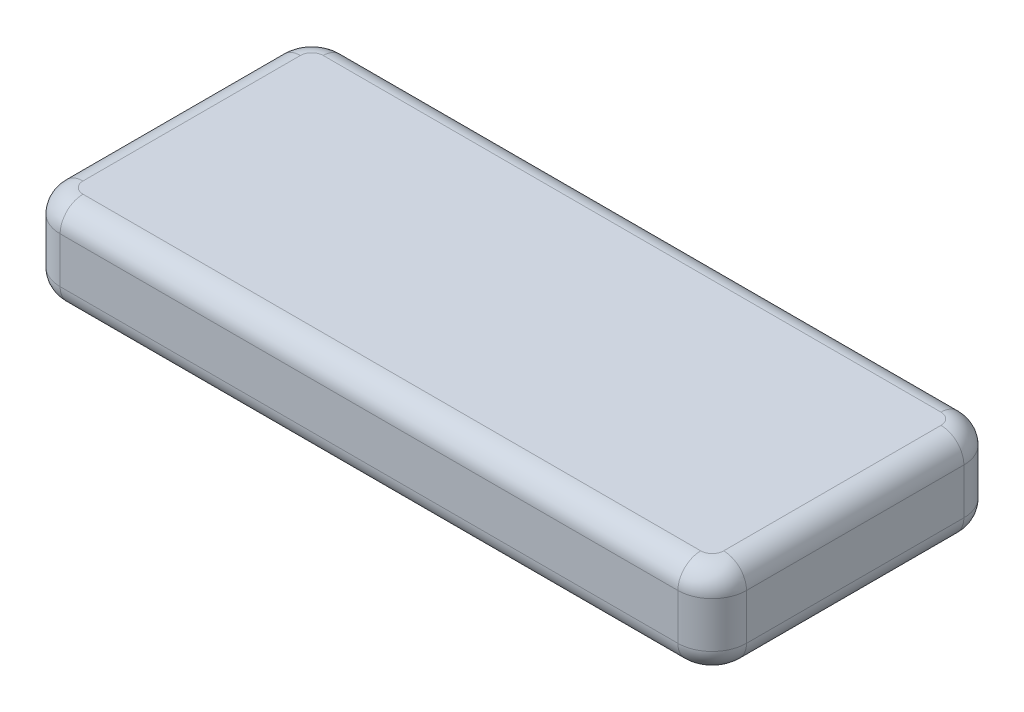
SolidWorks part; units mm, degrees
material "ABS"
ref_plane "前视基准面" through (0, 0, 0) normal (0, 0, 1) x (1, 0, 0)
ref_plane "上视基准面" through (0, 0, 0) normal (0, 1, 0) x (1, 0, 0)
ref_plane "右视基准面" through (0, 0, 0) normal (1, 0, 0) x (0, 0, -1)
other "Configuration Table"
sketch "草图1" plane through (0, 0, 0) normal (0, 1, 0) x (1, 0, 0)
  line L1 (-27, -12.5) -> (27, -12.5)
  line L2 (-30, -9.5) -> (-30, 9.5)
  line L3 (-27, 12.5) -> (27, 12.5)
  line L4 (30, -9.5) -> (30, 9.5)
  line L5 (-30, -12.5) -> (30, 12.5) construction
  line L6 (-30, 12.5) -> (30, -12.5) construction
  arc A0 (27, -12.5) -> (30, -9.5) centre (27, -9.5) ccw
  arc A1 (-27, -12.5) -> (-30, -9.5) centre (-27, -9.5) cw
  arc A2 (30, 9.5) -> (27, 12.5) centre (27, 9.5) ccw
  arc A3 (-27, 12.5) -> (-30, 9.5) centre (-27, 9.5) ccw
  point P0 (0, 0)
  dimension "D3" = 3
  dimension "D1" = 60
  dimension "D2" = 25
extrude "凸台-拉伸1" add sketch "草图1" along normal mid plane 8
fillet "圆角1" radius 2 16 edges at (-29.1213, 4, 11.6213) (-30, 4, 0) (-29.1213, 4, -11.6213) (0, 4, -12.5) (29.1213, 4, -11.6213) (30, 4, 0) (29.1213, 4, 11.6213) (30, -4, 0) (29.1213, -4, -11.6213) (0, -4, -12.5) (-29.1213, -4, -11.6213) (-30, -4, 0) (-29.1213, -4, 11.6213) (0, -4, 12.5) (29.1213, -4, 11.6213) (0, 4, 12.5)
